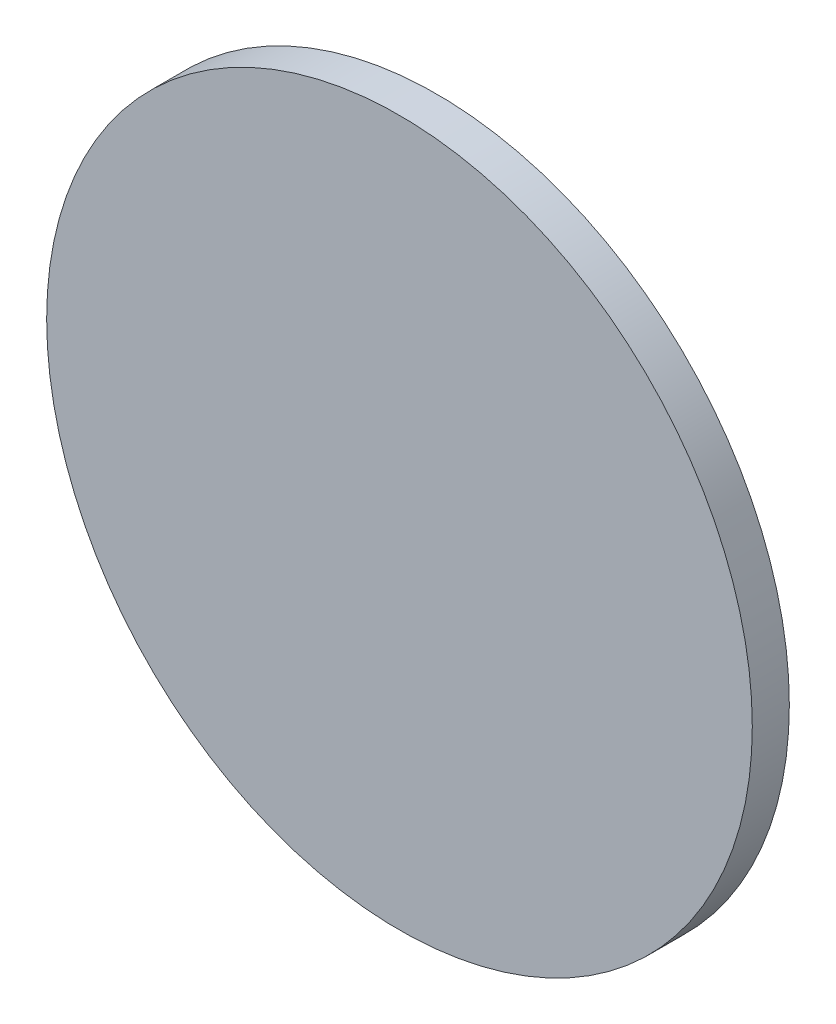
SolidWorks part; units mm, degrees
ref_plane "Front Plane" through (0, 0, 0) normal (0, 0, 1) x (1, 0, 0)
ref_plane "Top Plane" through (0, 0, 0) normal (0, 1, 0) x (1, 0, 0)
ref_plane "Right Plane" through (0, 0, 0) normal (1, 0, 0) x (0, 0, -1)
sketch "Sketch1" plane through (0, 0, 0) normal (0, 0, 1) x (1, 0, 0)
  circle A0 centre (0, 0) radius 9.525 construction
  circle A1 centre (0, 0) radius 9.525
extrude "Boss-Extrude1" add sketch "Sketch1" along normal blind 1
